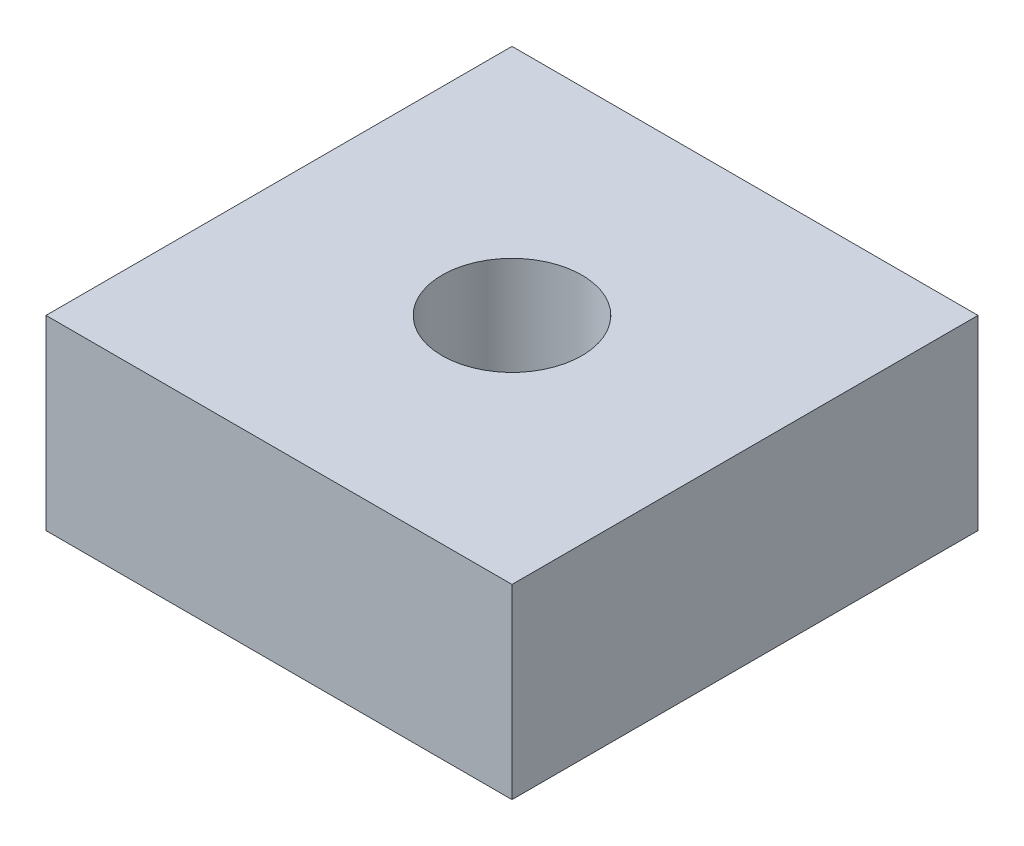
SolidWorks part; units mm, degrees
ref_plane "Front Plane" through (0, 0, 0) normal (0, 0, 1) x (1, 0, 0)
ref_plane "Top Plane" through (0, 0, 0) normal (0, 1, 0) x (1, 0, 0)
ref_plane "Right Plane" through (0, 0, 0) normal (1, 0, 0) x (0, 0, -1)
sketch "Sketch1" plane through (0, 0, 0) normal (0, 1, 0) x (1, 0, 0)
  line L1 (-5, 5) -> (5, 5)
  line L2 (-5, 5) -> (-5, -5)
  line L3 (-5, -5) -> (5, -5)
  line L4 (5, 5) -> (5, -5)
  line L5 (-5, 5) -> (5, -5) construction
  line L6 (-5, -5) -> (5, 5) construction
  circle A0 centre (0, 0) radius 1.5
  point P0 (0, 0)
  dimension "D3" = 3
  dimension "D1" = 10
  dimension "D2" = 10
extrude "Boss-Extrude1" add sketch "Sketch1" along normal blind 4
